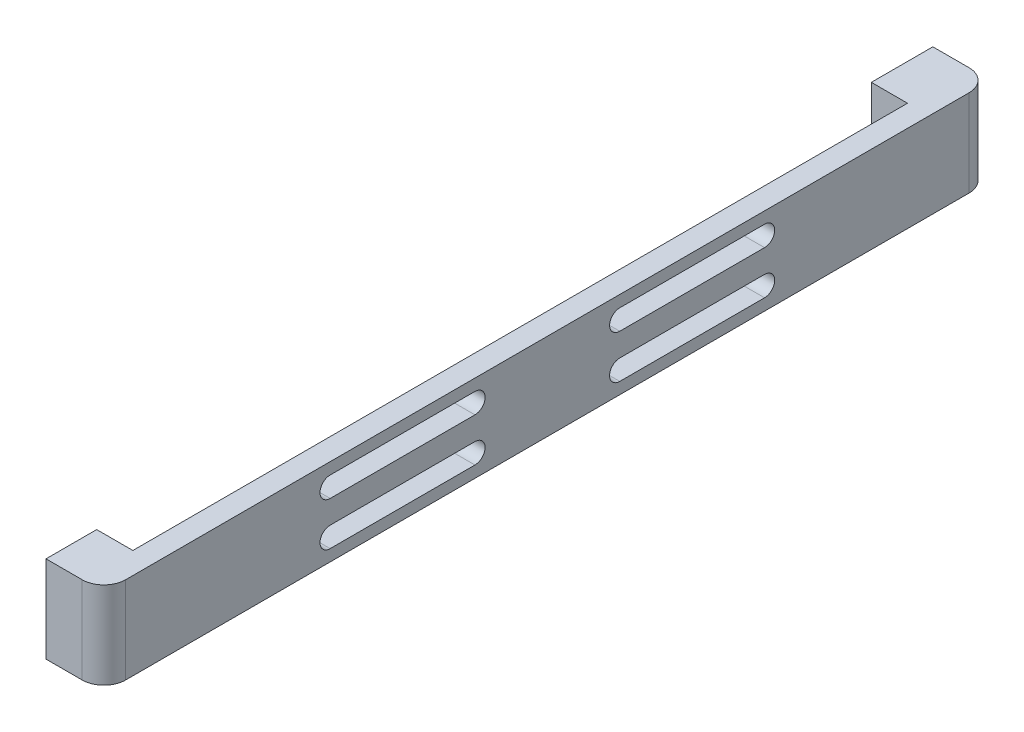
SolidWorks part; units mm, degrees
ref_plane "Front Plane" through (0, 0, 0) normal (0, 0, 1) x (1, 0, 0)
ref_plane "Top Plane" through (0, 0, 0) normal (0, 1, 0) x (1, 0, 0)
ref_plane "Right Plane" through (0, 0, 0) normal (1, 0, 0) x (0, 0, -1)
sketch "Sketch1" plane through (0, 0, 0) normal (1, 0, 0) x (0, 0, -1)
  line L1 (53.5, -6) -> (-53.5, -6)
  line L2 (53.5, -6) -> (53.5, 6)
  line L3 (53.5, 6) -> (-53.5, 6)
  line L4 (-53.5, -6) -> (-53.5, 6)
  line L5 (53.5, -6) -> (-53.5, 6) construction
  line L6 (53.5, 6) -> (-53.5, -6) construction
  line L7 (-53.5, 6) -> (-60.5, 6)
  line L8 (-53.5, 6) -> (-53.5, -6)
  line L9 (-53.5, -6) -> (-60.5, -6)
  line L10 (-60.5, 6) -> (-60.5, -6)
  line L11 (53.5, 6) -> (62, 6)
  line L12 (53.5, 6) -> (53.5, -6)
  line L13 (53.5, -6) -> (62, -6)
  line L14 (62, 6) -> (62, -6)
  point P0 (0, 0)
  dimension "D1" = 107
  dimension "D2" = 7
  dimension "D3" = 8.5
  dimension "D4" = 12
extrude "Boss-Extrude1" add sketch "Sketch1" along normal blind 5 contours L7 L10 L9 L4 | L14 L11 L2 L13
sketch "Sketch3" plane through (5, 0, 0) normal (1, 0, 0) x (0, 0, -1)
  line L1 (-60.5, 6) -> (62, 6)
  line L2 (-60.5, 6) -> (-60.5, -6)
  line L3 (-60.5, -6) -> (62, -6)
  line L4 (62, 6) -> (62, -6)
extrude "Boss-Extrude2" add sketch "Sketch3" along normal blind 3
sketch "Sketch4" plane through (8, 0, 0) normal (1, 0, 0) x (0, 0, -1)
  line L0 (-60.5, 0) -> (62, 0) construction
  line L1 (-60.5, 6) -> (-60.5, -6) construction
  line L2 (62, -6) -> (62, 6) construction
  line L3 (0.75, 6) -> (0.75, -6) construction
  line L4 (62, 6) -> (-60.5, 6) construction
  line L5 (-60.5, -6) -> (62, -6) construction
  line L6 (-29.25, 3) -> (-9.25, 3) construction
  line L7 (-19.25, -3) -> (20.75, -3) construction
  line L8 (-19.25, -3) -> (-19.25, 3) construction
  line L9 (-19.25, 3) -> (20.75, 3) construction
  line L10 (20.75, -3) -> (20.75, 3) construction
  line L11 (-19.25, -3) -> (20.75, 3) construction
  line L12 (-19.25, 3) -> (20.75, -3) construction
  line L13 (-29.25, 4.4) -> (-9.25, 4.4)
  line L14 (-29.25, 1.6) -> (-9.25, 1.6)
  line L15 (30.75, 3) -> (10.75, 3) construction
  line L16 (30.75, 1.6) -> (10.75, 1.6)
  line L17 (30.75, 4.4) -> (10.75, 4.4)
  line L18 (30.75, -3) -> (10.75, -3) construction
  line L19 (30.75, -4.4) -> (10.75, -4.4)
  line L20 (30.75, -1.6) -> (10.75, -1.6)
  line L21 (-29.25, -3) -> (-9.25, -3) construction
  line L22 (-29.25, -1.6) -> (-9.25, -1.6)
  line L23 (-29.25, -4.4) -> (-9.25, -4.4)
  circle A0 centre (-19.25, 3) radius 1.4
  circle A1 centre (-19.25, -3) radius 1.4
  circle A2 centre (20.75, -3) radius 1.4
  circle A3 centre (20.75, 3) radius 1.4
  arc A4 (-29.25, 4.4) -> (-29.25, 1.6) centre (-29.25, 3) ccw
  arc A5 (-9.25, 1.6) -> (-9.25, 4.4) centre (-9.25, 3) ccw
  arc A6 (30.75, 1.6) -> (30.75, 4.4) centre (30.75, 3) ccw
  arc A7 (10.75, 4.4) -> (10.75, 1.6) centre (10.75, 3) ccw
  arc A8 (30.75, -4.4) -> (30.75, -1.6) centre (30.75, -3) ccw
  arc A9 (10.75, -1.6) -> (10.75, -4.4) centre (10.75, -3) ccw
  arc A10 (-29.25, -1.6) -> (-29.25, -4.4) centre (-29.25, -3) ccw
  arc A11 (-9.25, -4.4) -> (-9.25, -1.6) centre (-9.25, -3) ccw
  point P12 (0.75, 0)
  point P23 (-19.25, 3)
  point P29 (20.75, 3)
  point P36 (20.75, -3)
  point P43 (-19.25, -3)
  point P49 (0, 0)
  point P50 (0, 0)
  point P51 (0, 0)
  dimension "D1" = 2.8
  dimension "D2" = 40
  dimension "D3" = 6
  dimension "D4" = 20
extrude "Cut-Extrude1" cut sketch "Sketch4" against normal blind 3 contours L13 A4 L14 A0 | A0 | L14 A5 L13 A0 | L23 A11 L22 A1 | A1 | L22 A10 L23 A1 | L20 A9 L19 A2 | L17 A7 L16 A3 | A3 | L16 A6 L17 A3 | L19 A8 L20 A2 | A2
fillet "Fillet1" radius 3 2 edges at (8, 0, -62) (8, 0, 60.5)
